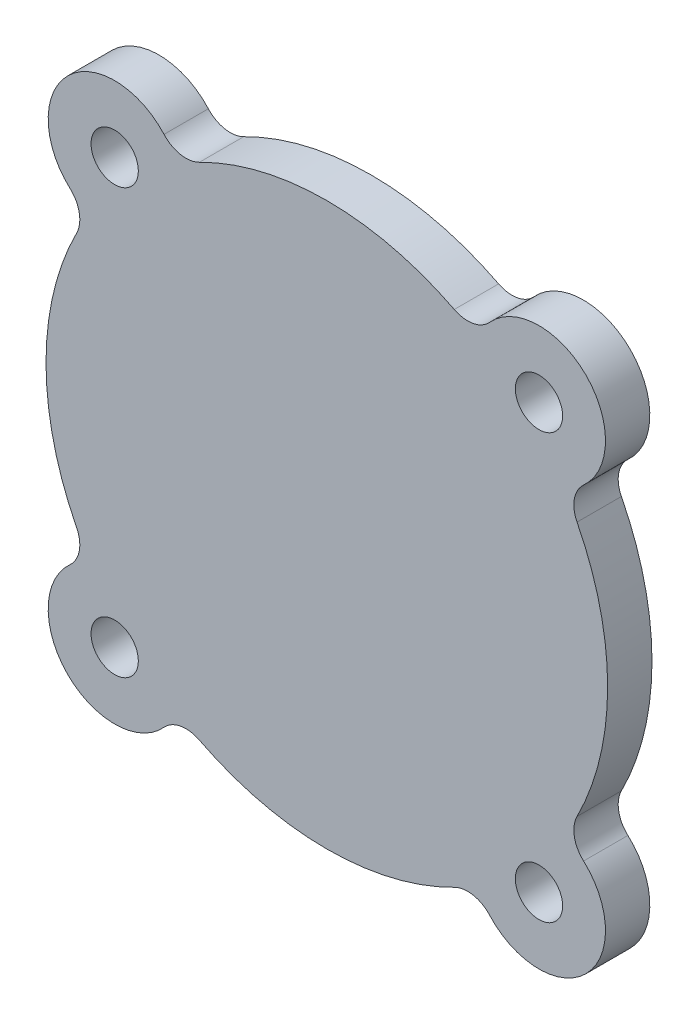
SolidWorks part; units mm, degrees
material "ﾎﾟﾘｶｰﾎﾞﾈｰﾄ(PC)高粘度"
ref_plane "Front Plane" through (0, 0, 0) normal (0, 0, 1) x (1, 0, 0)
ref_plane "Top Plane" through (0, 0, 0) normal (0, 1, 0) x (1, 0, 0)
ref_plane "Right Plane" through (0, 0, 0) normal (1, 0, 0) x (0, 0, -1)
sketch "ｽｹｯﾁ1" plane through (0, 0, 0) normal (0, 0, 1) x (1, 0, 0)
  circle A0 centre (0, 0) radius 19
  dimension "D1" = 38
extrude "ﾎﾞｽ - 押し出し1" add sketch "ｽｹｯﾁ1" along normal blind 3
sketch "ｽｹｯﾁ2" plane through (0, 0, 0) normal (0, 0, -1) x (-1, 0, 0)
  circle A0 centre (0, 0) radius 11.7
  circle A1 centre (0, 0) radius 15.8
  dimension "D1" = 23.4
  dimension "D2" = 31.6
extrude "ｶｯﾄ - 押し出し1" cut sketch "ｽｹｯﾁ2" against normal blind 2.4
sketch "ｽｹｯﾁ3" plane through (0, 0, 3) normal (0, 0, 1) x (1, 0, 0)
  line L1 (0, 0) -> (-23.5858, 23.5858) construction
  line L3 (0, 0) -> (0, 14.84) construction
  line L4 (0, 0) -> (0, 119.4538) construction
  circle A0 centre (-14.3543, 14.3543) radius 4.5
  circle A1 centre (-14.3543, 14.3543) radius 1.6 construction
  circle A3 centre (0, 0) radius 15.8 construction
  circle A4 centre (14.3543, 14.3543) radius 4.5
  circle A5 centre (14.3543, 14.3543) radius 1.6 construction
  circle A6 centre (14.3543, -14.3543) radius 4.5
  circle A7 centre (14.3543, -14.3543) radius 1.6 construction
  circle A8 centre (-14.3543, -14.3543) radius 4.5
  circle A9 centre (-14.3543, -14.3543) radius 1.6 construction
  point P24 (0, 0)
  dimension "D1" = 9
  dimension "D2" = 3.2
  dimension "D3" = 4
  dimension "D4" = 45
extrude "ﾎﾞｽ - 押し出し2" add sketch "ｽｹｯﾁ3" against normal up to surface (3 mm away) up to face at (-15.8, 0, 0)
hole_wizard "M3 すきま穴1" positions "ｽｹｯﾁ5" profile "ｽｹｯﾁ6" hole size "M3" standard "JIS" end condition through all
sketch "ｽｹｯﾁ5" plane through (0, 0, 3) normal (0, 0, 1) x (1, 0, 0)
  point P0 (-14.3543, 14.3543)
  point P2 (-14.3543, -14.3543)
  point P5 (14.3543, 14.3543)
  point P11 (14.3543, -14.3543)
sketch "ｽｹｯﾁ6" plane through (-14.3543, 14.3543, 3) normal (1, 0, 0) x (0, -1, 0)
  line L0 (0, 0) -> (0, 3)
  line L1 (0, 3) -> (1.6, 3)
  line L2 (1.6, 3) -> (1.6, 0)
  line L5 (1.6, 0) -> (0, 0)
  line L11 (0, -6.35) -> (0, 107.95) construction
  dimension "通し穴の直径" = 3.2
  dimension "通し穴の深さ" = 3
fillet "ﾌｨﾚｯﾄ1" radius 2 8 edges at (10.1824, -16.0412, 1.5) (16.0412, -10.1824, 1.5) (16.0412, 10.1824, 1.5) (10.1824, 16.0412, 1.5) (-10.1824, 16.0412, 1.5) (-16.0412, 10.1824, 1.5) (-16.0412, -10.1824, 1.5) (-10.1824, -16.0412, 1.5)
